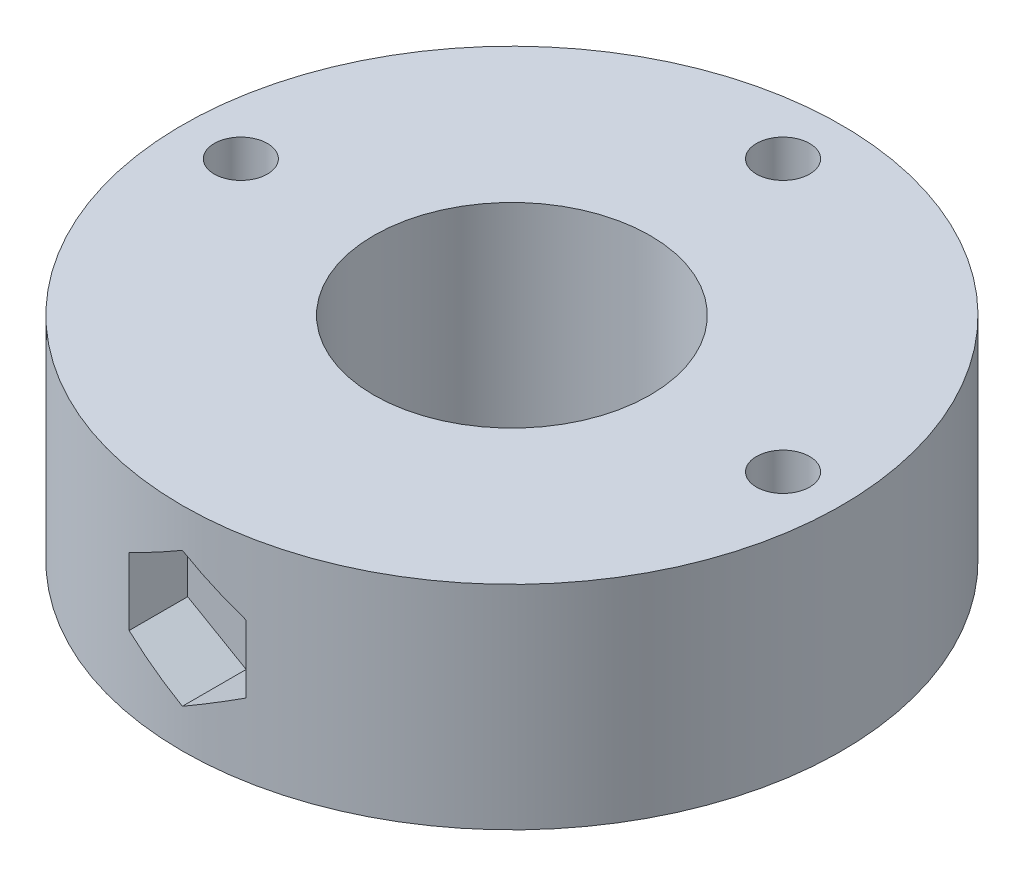
SolidWorks part; units mm, degrees
ref_plane "Front Plane" through (0, 0, 0) normal (0, 0, 1) x (1, 0, 0)
ref_plane "Top Plane" through (0, 0, 0) normal (0, 1, 0) x (1, 0, 0)
ref_plane "Right Plane" through (0, 0, 0) normal (1, 0, 0) x (0, 0, -1)
sketch "Sketch1" plane through (0, 0, 0) normal (0, 1, 0) x (1, 0, 0)
  circle A0 centre (0, 0) radius 31
  circle A1 centre (0, 0) radius 13
  circle A2 centre (0, 0) radius 25.5 construction
  circle A3 centre (0, 25.5) radius 2.5
  circle A4 centre (-25.5, 0) radius 2.5
  circle A5 centre (25.5, 0) radius 2.5
  dimension "D1" = 62
  dimension "D2" = 26
  dimension "D3" = 51
  dimension "D4" = 5
  dimension "D5" = 5
  dimension "D6" = 5
extrude "Boss-Extrude1" add sketch "Sketch1" along normal blind 20
sketch "Sketch2" plane through (0, 0, 0) normal (0, 0, 1) x (1, 0, 0)
  line L0 (0, 0) -> (0, 20) construction
  line L1 (31, 20) -> (-31, 20) construction
  line L3 (0, 16.3509) -> (-5.5, 13.1754)
  line L4 (-5.5, 13.1754) -> (-5.5, 6.8246)
  line L5 (-5.5, 6.8246) -> (0, 3.6491)
  line L6 (0, 3.6491) -> (5.5, 6.8246)
  line L7 (5.5, 6.8246) -> (5.5, 13.1754)
  line L8 (5.5, 13.1754) -> (0, 16.3509)
  circle A0 centre (0, 10) radius 5.5 construction
  circle A1 centre (0, 10) radius 3 construction
  dimension "D1" = 11
ref_plane "Plane1" through (0, 0, 40) normal (0, 0, 1) x (1, 0, 0)
sketch "Sketch3" plane through (0, 0, 40) normal (0, 0, 1) x (1, 0, 0)
  line L0 (-5.5, 6.8246) -> (0, 3.6491) construction
  line L1 (0, 3.6491) -> (5.5, 6.8246) construction
  line L2 (5.5, 6.8246) -> (5.5, 13.1754) construction
  line L3 (5.5, 13.1754) -> (0, 16.3509) construction
  line L4 (0, 16.3509) -> (-5.5, 13.1754) construction
  line L5 (-5.5, 13.1754) -> (-5.5, 6.8246) construction
  line L6 (-5.5, 6.8246) -> (0, 3.6491)
  line L7 (0, 3.6491) -> (5.5, 6.8246)
  line L8 (5.5, 6.8246) -> (5.5, 13.1754)
  line L9 (5.5, 13.1754) -> (0, 16.3509)
  line L10 (0, 16.3509) -> (-5.5, 13.1754)
  line L11 (-5.5, 13.1754) -> (-5.5, 6.8246)
extrude "Cut-Extrude1" cut sketch "Sketch3" against normal blind 15
